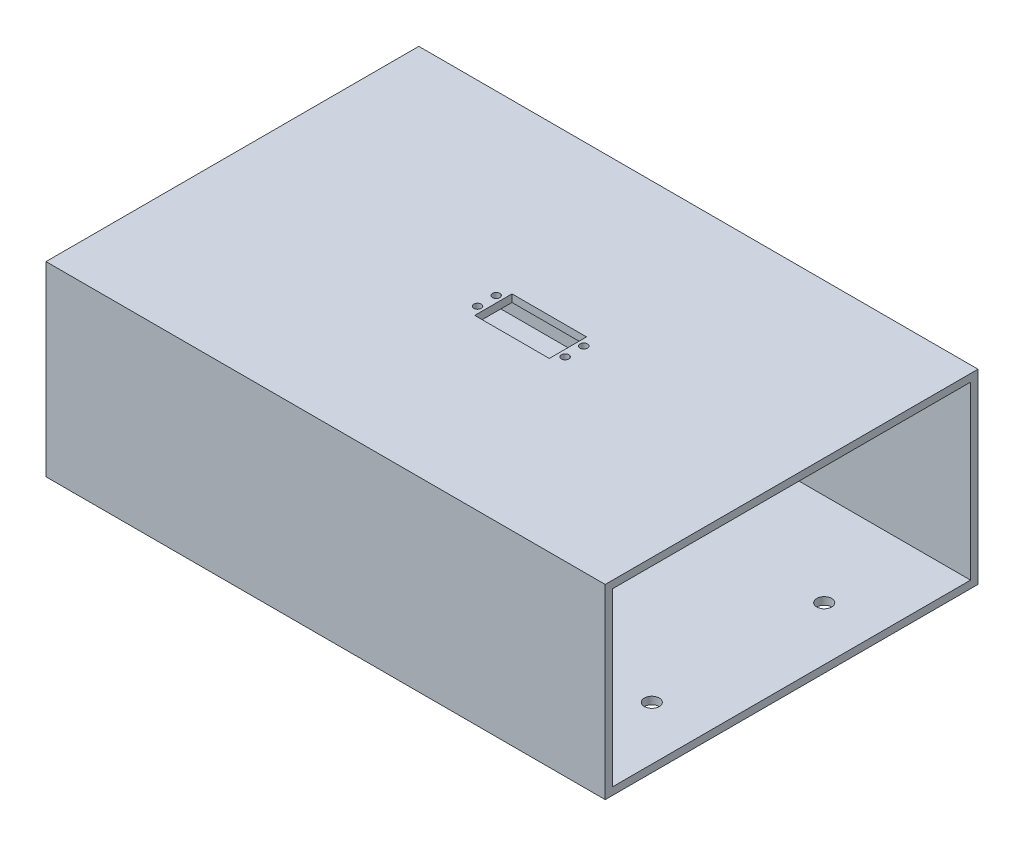
SolidWorks part; units mm, degrees
ref_plane "Ön Düzlem" through (0, 0, 0) normal (0, 0, 1) x (1, 0, 0)
ref_plane "Üst Düzlem" through (0, 0, 0) normal (0, 1, 0) x (1, 0, 0)
ref_plane "Sağ Düzlem" through (0, 0, 0) normal (1, 0, 0) x (0, 0, -1)
sketch "Çizim1" plane through (0, 0, 0) normal (0, 0, 1) x (1, 0, 0)
  line L1 (0, 0) -> (-300, 0)
  line L2 (0, 0) -> (0, 100)
  line L3 (0, 100) -> (-300, 100)
  line L4 (-300, 0) -> (-300, 100)
  dimension "D1" = 100
  dimension "D2" = 300
extrude "Yükseklik-Ekstrüzyon1" add sketch "Çizim1" along normal blind 200
shell "İç Boşaltma1" thickness 4
sketch "Çizim2" plane through (0, 0, 0) normal (0, -1, 0) x (1, 0, 0)
  line L1 (-300, 200) -> (0, 200) construction
  line L2 (-300, 200) -> (-300, 0) construction
  line L5 (-150, 200) -> (-150, 171.4217) construction
  circle A0 centre (-271.25, 146.25) radius 4
  circle A1 centre (-178.75, 146.25) radius 4
  circle A2 centre (-28.75, 146.25) radius 4
  circle A3 centre (-121.25, 146.25) radius 4
  circle A4 centre (-271.25, 53.75) radius 4
  circle A5 centre (-178.75, 53.75) radius 4
  circle A6 centre (-121.25, 53.75) radius 4
  circle A7 centre (-28.75, 53.75) radius 4
  dimension "D1" = 53.75
  dimension "D2" = 53.75
  dimension "D3" = 28.75
  dimension "D4" = 92.5
  dimension "D5" = 8
  dimension "D6" = 8
  dimension "D8" = 92.5
  dimension "D7" = 2
extrude "Kes-Ekstrüzyon1" cut sketch "Çizim2" against normal up to next
sketch "Çizim3" plane through (0, 100, 0) normal (0, 1, 0) x (1, 0, 0)
  line L0 (0, -200) -> (0, 0) construction
  line L4 (-160, -90) -> (-120, -90)
  line L5 (-160, -90) -> (-160, -110)
  line L6 (-160, -110) -> (-120, -110)
  line L7 (-120, -90) -> (-120, -110)
  line L8 (-160, -90) -> (-120, -110) construction
  line L9 (-160, -110) -> (-120, -90) construction
  line L10 (-140, -100) -> (-140, -106.5002) construction
  circle A0 centre (-116.5, -95) radius 2
  circle A1 centre (-116.5, -105) radius 2
  circle A2 centre (-163.5, -105) radius 2
  circle A3 centre (-163.5, -95) radius 2
  point P6 (-140, -100)
  dimension "D5" = 3.5
  dimension "D1" = 40
  dimension "D2" = 20
  dimension "D3" = 120
  dimension "D4" = 3.5
extrude "Kes-Ekstrüzyon2" cut sketch "Çizim3" against normal up to next
